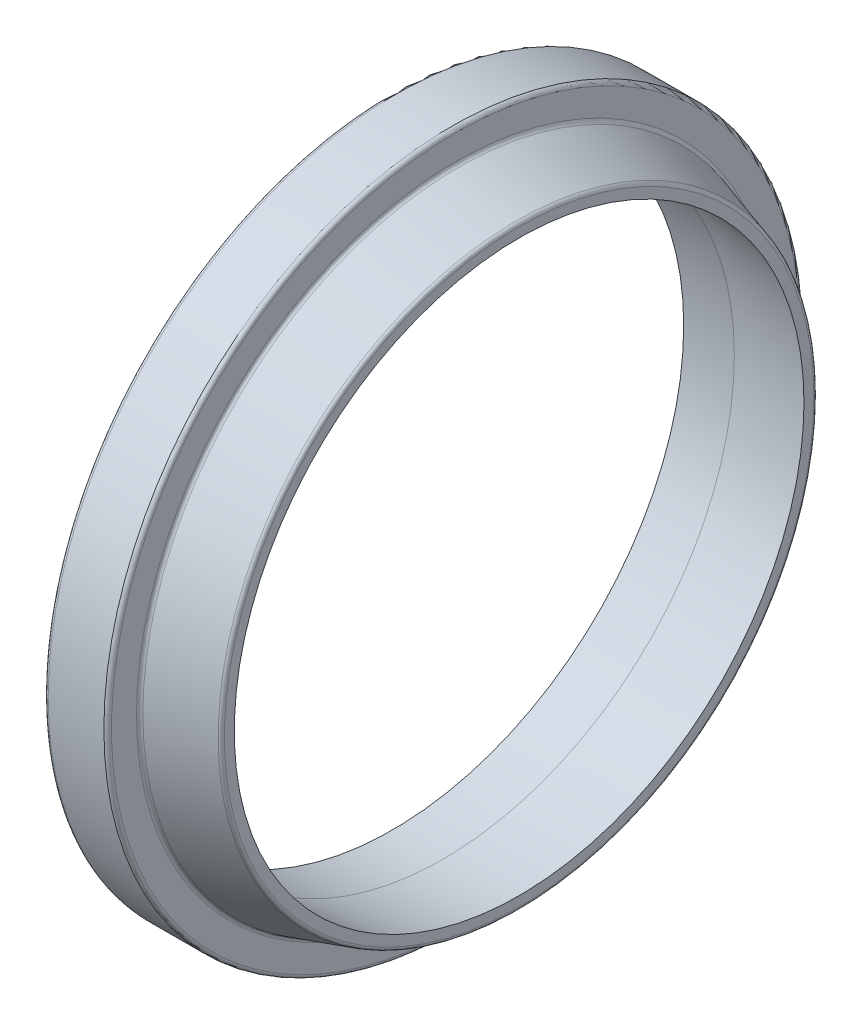
SolidWorks part; units mm, degrees
ref_plane "Front Plane" through (0, 0, 0) normal (0, 0, 1) x (1, 0, 0)
ref_plane "Top Plane" through (0, 0, 0) normal (0, 1, 0) x (1, 0, 0)
ref_plane "Right Plane" through (0, 0, 0) normal (1, 0, 0) x (0, 0, -1)
sketch "Sketch1" plane through (0, 0, 0) normal (0, 0, 1) x (1, 0, 0)
  line L0 (0, 0) -> (10, 0) construction
  line L2 (0.3, 5) -> (4.7, 5)
  line L3 (5, 4.7) -> (5, 2.7232)
  line L4 (5.2138, 2.4359) -> (9.7862, 1.0641)
  line L5 (10, 0.7768) -> (10, 0)
  line L6 (0, 4.7) -> (0, 0.5)
  line L7 (0, 0.5) -> (4, 0.5)
  line L8 (4, 0.5) -> (10, 0)
  line L9 (10, 0) -> (10, -22.5) construction
  line L10 (10, -22.5) -> (2.6375, -22.5) construction
  arc A0 (5, 4.7) -> (4.7, 5) centre (4.7, 4.7) ccw
  arc A1 (0.3, 5) -> (0, 4.7) centre (0.3, 4.7) ccw
  arc A2 (5.2138, 2.4359) -> (5, 2.7232) centre (5.3, 2.7232) cw
  arc A3 (10, 0.7768) -> (9.7862, 1.0641) centre (9.7, 0.7768) ccw
  point P11 (5, 5)
  point P14 (0, 5)
  point P17 (5, 2.5)
  point P20 (10, 1)
  dimension "D8" = 0.3
  dimension "D9" = 0.3
  dimension "D10" = 0.3
  dimension "D1" = 10
  dimension "D2" = 5
  dimension "D3" = 5
  dimension "D4" = 4
  dimension "D5" = 2.5
  dimension "D6" = 4.5
  dimension "D7" = 4
  dimension "D11" = 22.5
revolve "Revolve1" add sketch "Sketch1" angle 360 about L10
